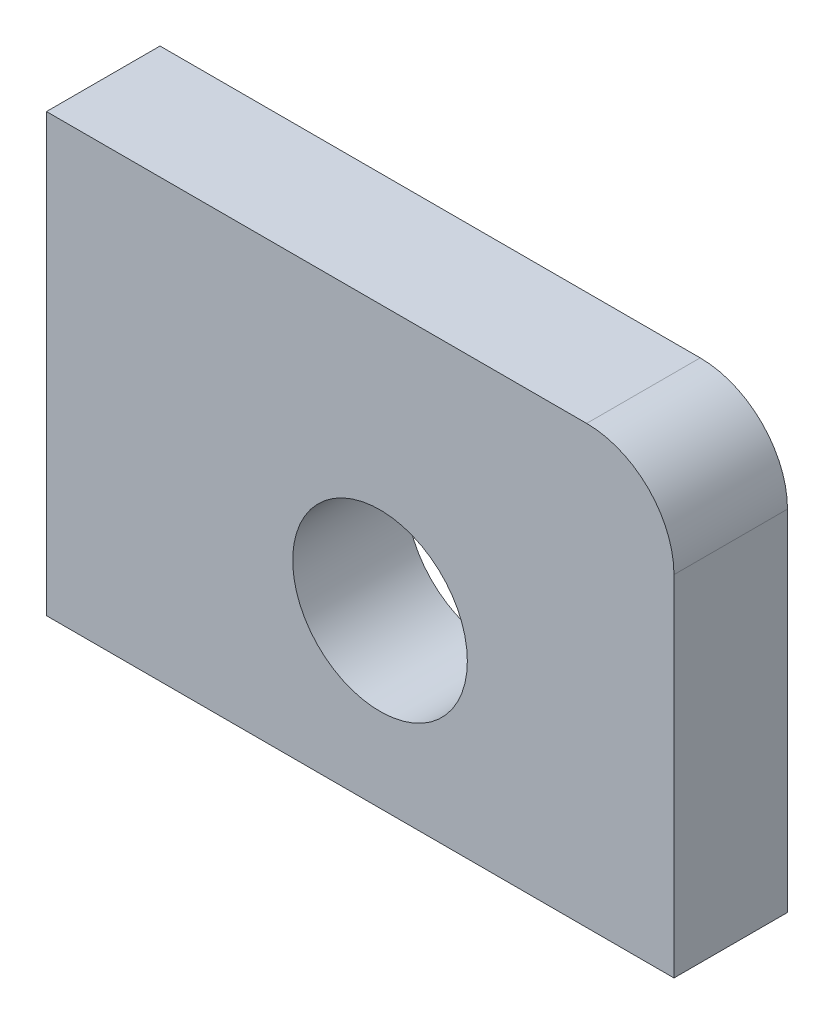
SolidWorks part; units mm, degrees
ref_plane "前视基准面" through (0, 0, 0) normal (0, 0, 1) x (1, 0, 0)
ref_plane "上视基准面" through (0, 0, 0) normal (0, 1, 0) x (1, 0, 0)
ref_plane "右视基准面" through (0, 0, 0) normal (1, 0, 0) x (0, 0, -1)
sketch "草图2" plane through (0, 0, 0) normal (0, 0, 1) x (1, 0, 0)
  line L1 (-58.2739, 30.3952) -> (41.7261, 30.3952)
  line L2 (-58.2739, 30.3952) -> (-58.2739, -19.6048)
  line L3 (-58.2739, -19.6048) -> (41.7261, -19.6048)
  line L4 (41.7261, 30.3952) -> (41.7261, -19.6048)
extrude "凸台-拉伸1" add sketch "草图2" along normal blind 13
fillet "圆角1" radius 10 1 edges at (41.7261, 30.3952, 6.5)
sketch "草图3" plane through (0, 0, 13) normal (0, 0, 1) x (1, 0, 0)
  circle A0 centre (8.0646, 0) radius 10
extrude "切除-拉伸1" cut sketch "草图3" against normal blind 13
sketch "草图4" plane through (0, 0, 13) normal (0, 0, 1) x (1, 0, 0)
  line L0 (-58.2739, 30.3952) -> (-58.2739, -19.6048) construction
  line L1 (-58.2739, 30.3952) -> (-30.1286, 30.3952)
  line L2 (-58.2739, 30.3952) -> (-58.2739, -19.6048)
  line L3 (-58.2739, -19.6048) -> (-30.1286, -19.6048)
  line L4 (-30.1286, 30.3952) -> (-30.1286, -19.6048)
  line L5 (31.7261, 30.3952) -> (-58.2739, 30.3952) construction
  line L6 (-58.2739, -19.6048) -> (41.7261, -19.6048) construction
extrude "切除-拉伸2" cut sketch "草图4" against normal blind 13
